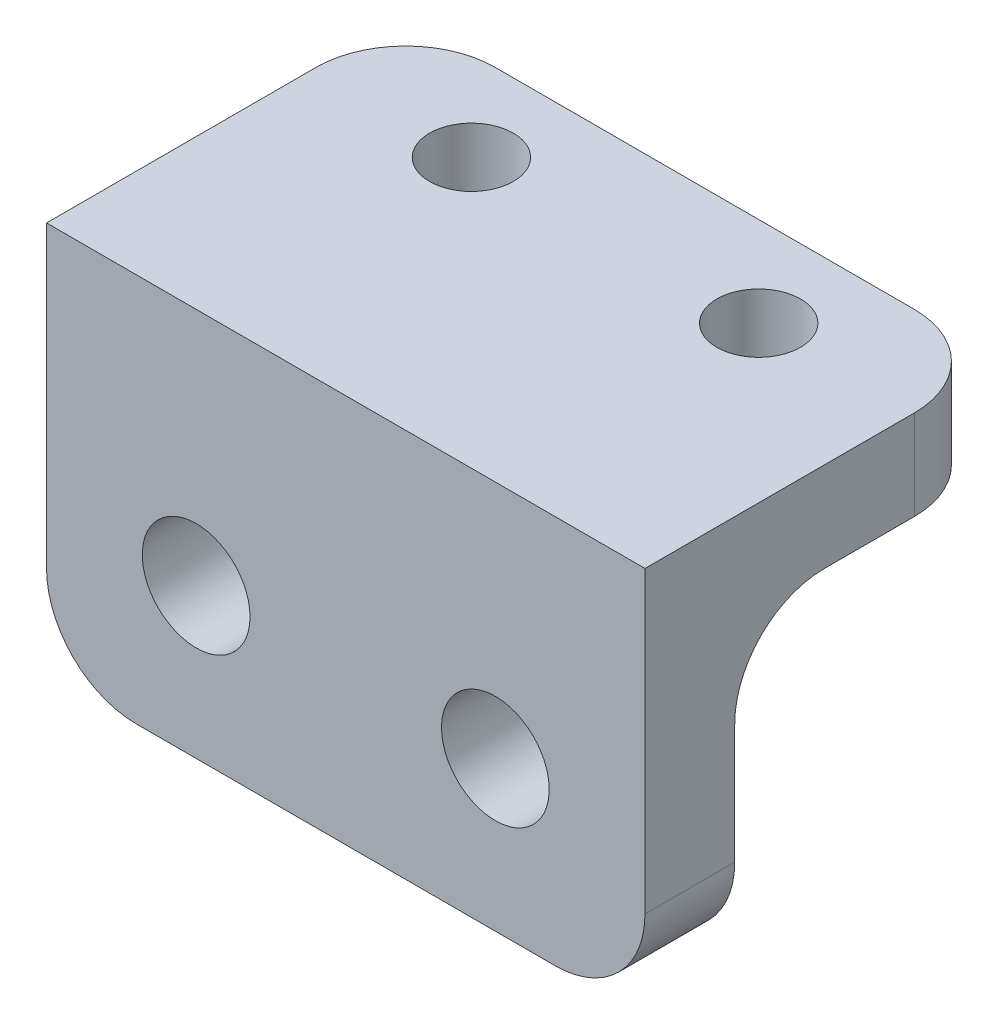
SolidWorks part; units mm, degrees
ref_plane "Front Plane" through (0, 0, 0) normal (0, 0, 1) x (1, 0, 0)
ref_plane "Top Plane" through (0, 0, 0) normal (0, 1, 0) x (1, 0, 0)
ref_plane "Right Plane" through (0, 0, 0) normal (1, 0, 0) x (0, 0, -1)
sketch "Sketch1" plane through (0, 0, 0) normal (0, 0, 1) x (1, 0, 0)
  line L0 (0, 5) -> (0, -5) construction
  line L1 (-10, -5) -> (10, -5)
  line L2 (-10, -5) -> (-10, 5)
  line L3 (-10, 5) -> (10, 5)
  line L4 (10, -5) -> (10, 5)
  line L5 (-10, -5) -> (10, 5) construction
  line L6 (-10, 5) -> (10, -5) construction
  circle A0 centre (-5, 0) radius 1.8
  circle A1 centre (5, 0) radius 1.8
  point P0 (0, 0)
  dimension "D3" = 3.6
  dimension "D1" = 20
  dimension "D2" = 10
  dimension "D4" = 5
extrude "Boss-Extrude1" add sketch "Sketch1" along normal blind 3
sketch "Sketch2" plane through (0, 5, 0) normal (0, 1, 0) x (1, 0, 0)
  line L0 (10, -3) -> (10, 0) construction
  line L1 (-10, -3) -> (10, -3)
  line L2 (-10, -3) -> (-10, 9)
  line L3 (-10, 9) -> (10, 9)
  line L4 (10, -3) -> (10, 9)
  line L5 (-10, -3) -> (10, 9) construction
  line L6 (-10, 9) -> (10, -3) construction
  line L7 (-199.9176, -53.7793) -> (282.7491, -53.7793) construction
  line L8 (0, 9) -> (0, -3) construction
  line L9 (-10, 3) -> (10, 3) construction
  circle A0 centre (4.8, 6) radius 1.4
  circle A1 centre (-4.8, 6) radius 1.4
  point P4 (0, 3)
  point P17 (0, 3)
  dimension "D3" = 2.8
  dimension "D1" = 12
  dimension "D2" = 4.8
  dimension "D4" = 3
extrude "Boss-Extrude2" add sketch "Sketch2" along normal blind 3
fillet "Fillet1" radius 3 5 edges at (-10, -5, 1.5) (10, -5, 1.5) (-10, 6.5, -9) (10, 6.5, -9) (0, 5, 0)
ref_plane "Plane1" through (0, 0, -15) normal (0, 0, -1) x (-1, 0, 0)
